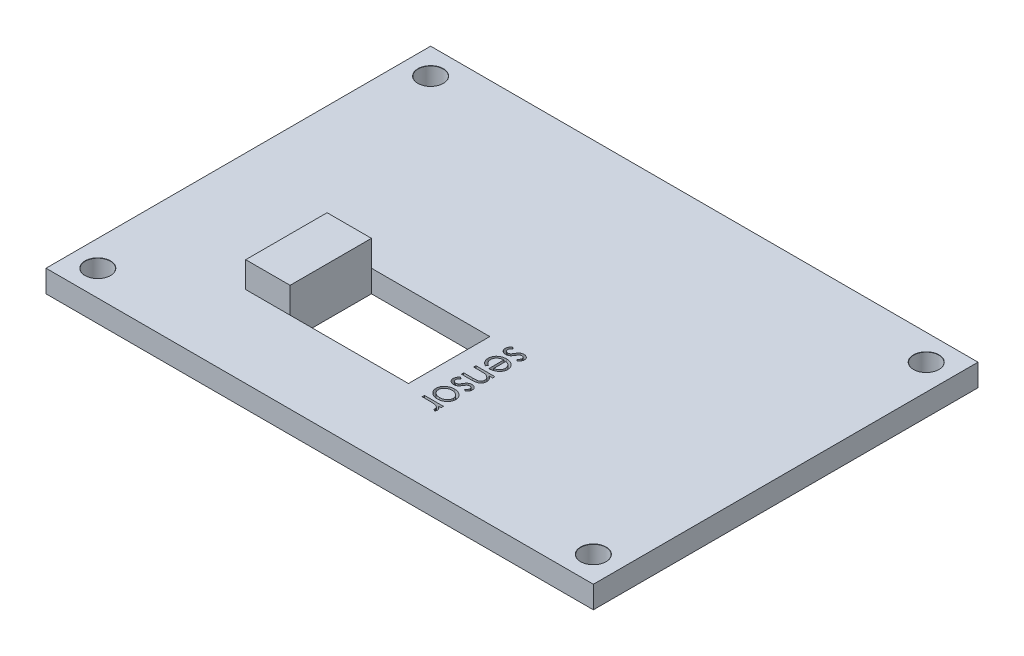
SolidWorks part; units mm, degrees
ref_plane "Front Plane" through (0, 0, 0) normal (0, 0, 1) x (1, 0, 0)
ref_plane "Top Plane" through (0, 0, 0) normal (0, 1, 0) x (1, 0, 0)
ref_plane "Right Plane" through (0, 0, 0) normal (1, 0, 0) x (0, 0, -1)
sketch "Sketch1" plane through (0, 0, 0) normal (0, 1, 0) x (1, 0, 0)
  line L1 (-37, 26) -> (37, 26)
  line L2 (-37, 26) -> (-37, -26)
  line L3 (-37, -26) -> (37, -26)
  line L4 (37, 26) -> (37, -26)
  line L5 (-37, 26) -> (37, -26) construction
  line L6 (-37, -26) -> (37, 26) construction
  point P0 (0, 0)
  dimension "D1" = 74
  dimension "D2" = 52
extrude "Boss-Extrude1" add sketch "Sketch1" along normal blind 3
sketch "Sketch2" plane through (0, 3, 0) normal (0, 1, 0) x (1, 0, 0)
  line L0 (37, 26) -> (-37, 26) construction
  line L1 (-37, 26) -> (-37, -26) construction
  line L2 (-37, -26) -> (37, -26) construction
  line L4 (37, -26) -> (37, 26) construction
  point P0 (33.5, 22.5)
  point P1 (-33.5, 22.5)
  point P2 (-33.5, -22.5)
  point P3 (33.5, -22.5)
  point P4 (0, 0)
  point P5 (0, 0)
  point P6 (0, 0)
  point P7 (0, 0)
  point P16 (37, -24.2069)
  dimension "D1" = 3.5
  dimension "D2" = 3.5
  dimension "D3" = 3.5
  dimension "D4" = 3.5
hole_wizard "M3 Clearance Hole1" positions "Sketch3" profile "Sketch4" hole size "M3" standard "ISO"
sketch "Sketch3" plane through (0, 3, 0) normal (0, 1, 0) x (1, 0, 0)
  point P0 (-33.5, 22.5)
  point P3 (-33.5, -22.5)
  point P6 (33.5, -22.5)
  point P9 (33.5, 22.5)
sketch "Sketch4" plane through (-33.5, 3, -22.5) normal (1, 0, 0) x (0, 0, 1)
  line L0 (0, 0) -> (0, 5.5215)
  line L1 (0, 5.5215) -> (1.7, 4.5)
  line L2 (1.7, 4.5) -> (1.7, 0.025)
  line L3 (1.7, 0.025) -> (1.725, 0)
  line L5 (1.725, 0) -> (0, 0)
  line L6 (-1.7, 0.025) -> (-1.725, 0) construction
  line L10 (0, 5.5215) -> (-1.7, 4.5) construction
  line L11 (0, -6.35) -> (0, 107.95) construction
  dimension "Hole Dia." = 3.4
  dimension "Hole Depth" = 4.5
  dimension "Near C'Sink Dia." = 3.45
  dimension "Near C'Sink Angle" = 90
  dimension "Drill Angle" = 118
sketch "Sketch5" plane through (0, 3, 0) normal (0, 1, 0) x (1, 0, 0)
  line L0 (-37, -26) -> (37, -26) construction
  line L1 (-21, -4) -> (1, -4)
  line L2 (-21, -4) -> (-21, -15)
  line L3 (-21, -15) -> (1, -15)
  line L4 (1, -4) -> (1, -15)
  line L5 (-21, -4) -> (1, -15) construction
  line L6 (-21, -15) -> (1, -4) construction
  line L7 (-37, 26) -> (-37, -26) construction
  line L8 (-15, -4) -> (-15, -15)
  point P0 (-10, -9.5)
  point P9 (-15, -4)
  point P10 (-15, -15)
  dimension "D1" = 22
  dimension "D2" = 11
  dimension "D3" = 11
  dimension "D4" = 16
  dimension "D5" = 6
extrude "Cut-Extrude1" cut sketch "Sketch5" against normal blind 23 contours L1 L8 L3 L4
sketch "Sketch7" plane through (0, 3, 0) normal (0, 1, 0) x (1, 0, 0)
  line L0 (-15, -4) -> (-15, -15)
  line L1 (-15, -4) -> (-21, -4)
  line L2 (-15, -15) -> (-21, -15)
  line L3 (-21, -4) -> (-21, -15)
  dimension "D1" = 6
extrude "Boss-Extrude2" add sketch "Sketch7" along normal blind 3.5
sketch "Sketch8" plane through (0, 0, 0) normal (0, -1, 0) x (1, 0, 0)
  line L0 (-15, 4) -> (-21, 4) construction
  line L2 (-21, 4) -> (-21, 15) construction
  point P0 (-19, 6)
  point P5 (-21.5157, 5.8802)
  point P6 (-18.5196, 6)
  dimension "D1" = 2
  dimension "D2" = 2
hole_wizard "M2.5 Clearance Hole2" positions "Sketch11" profile "Sketch12" hole size "M2.5" standard "ISO"
sketch "Sketch11" plane through (0, 0, 0) normal (0, -1, 0) x (-1, 0, 0)
  point P0 (19, -6)
sketch "Sketch12" plane through (-19, 0, 6) normal (1, 0, 0) x (0, 0, -1)
  line L0 (0, 0) -> (0, 5.8712)
  line L1 (0, 5.8712) -> (1.45, 5)
  line L2 (1.45, 5) -> (1.45, 0.025)
  line L3 (1.45, 0.025) -> (1.475, 0)
  line L5 (1.475, 0) -> (0, 0)
  line L6 (-1.45, 0.025) -> (-1.475, 0) construction
  line L10 (0, 5.8712) -> (-1.45, 5) construction
  line L11 (0, -6.35) -> (0, 107.95) construction
  dimension "Hole Dia." = 2.9
  dimension "Hole Depth" = 5
  dimension "Near C'Sink Dia." = 2.95
  dimension "Near C'Sink Angle" = 90
  dimension "Drill Angle" = 118
sketch "Sketch14" plane through (0, 3, 0) normal (0, 1, 0) x (1, 0, 0)
  text T0 "sensor" font "Century Gothic" height 3.5
extrude "Cut-Extrude2" cut sketch "Sketch14" against normal blind 1
equation "\"D2@Sketch2\"=\"D1@Sketch2\""
equation "\"D3@Sketch2\"=\"D1@Sketch2\""
equation "\"D4@Sketch2\"=\"D1@Sketch2\""
